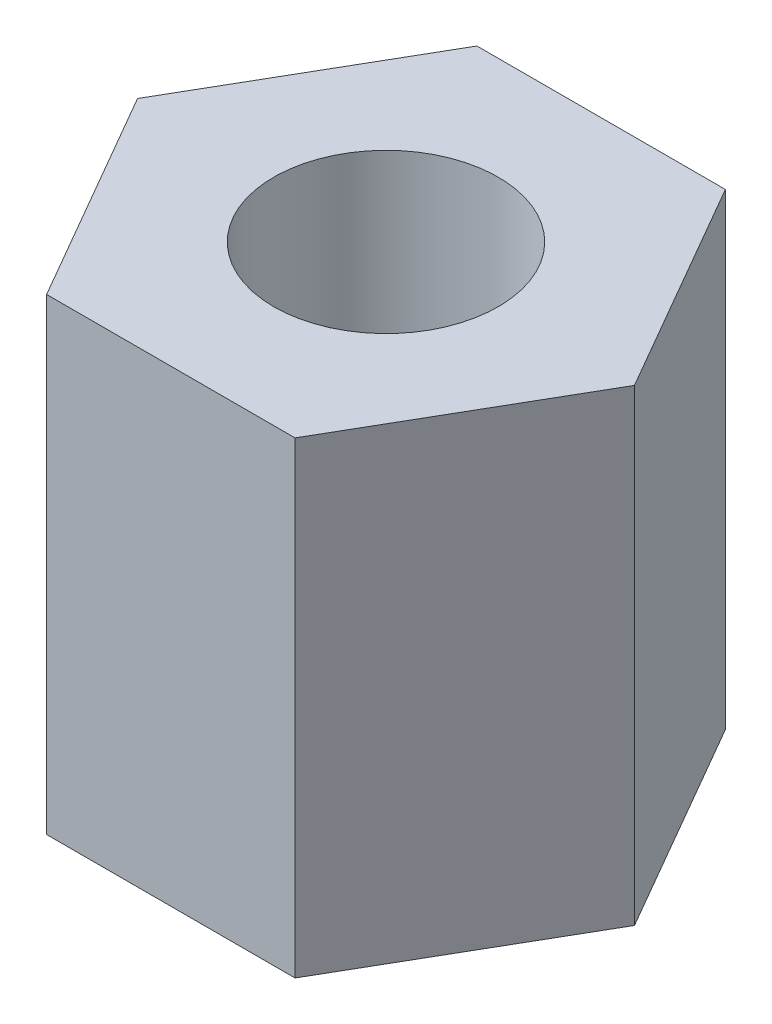
SolidWorks part; units mm, degrees
ref_plane "前视基准面" through (0, 0, 0) normal (0, 0, 1) x (1, 0, 0)
ref_plane "上视基准面" through (0, 0, 0) normal (0, 1, 0) x (1, 0, 0)
ref_plane "右视基准面" through (0, 0, 0) normal (1, 0, 0) x (0, 0, -1)
other "Configuration Table"
sketch "草图1" plane through (0, 0, 0) normal (0, 1, 0) x (1, 0, 0)
  line L1 (2.6558, 0) -> (1.3279, 2.3)
  line L2 (1.3279, 2.3) -> (-1.3279, 2.3)
  line L3 (-1.3279, 2.3) -> (-2.6558, 0)
  line L4 (-2.6558, 0) -> (-1.3279, -2.3)
  line L5 (-1.3279, -2.3) -> (1.3279, -2.3)
  line L6 (1.3279, -2.3) -> (2.6558, 0)
  circle A0 centre (0, 0) radius 2.3 construction
  circle A1 centre (0, 0) radius 1.2
  dimension "D2" = 2.4
  dimension "D1" = 4.6
extrude "凸台-拉伸1" add sketch "草图1" along normal blind 5
